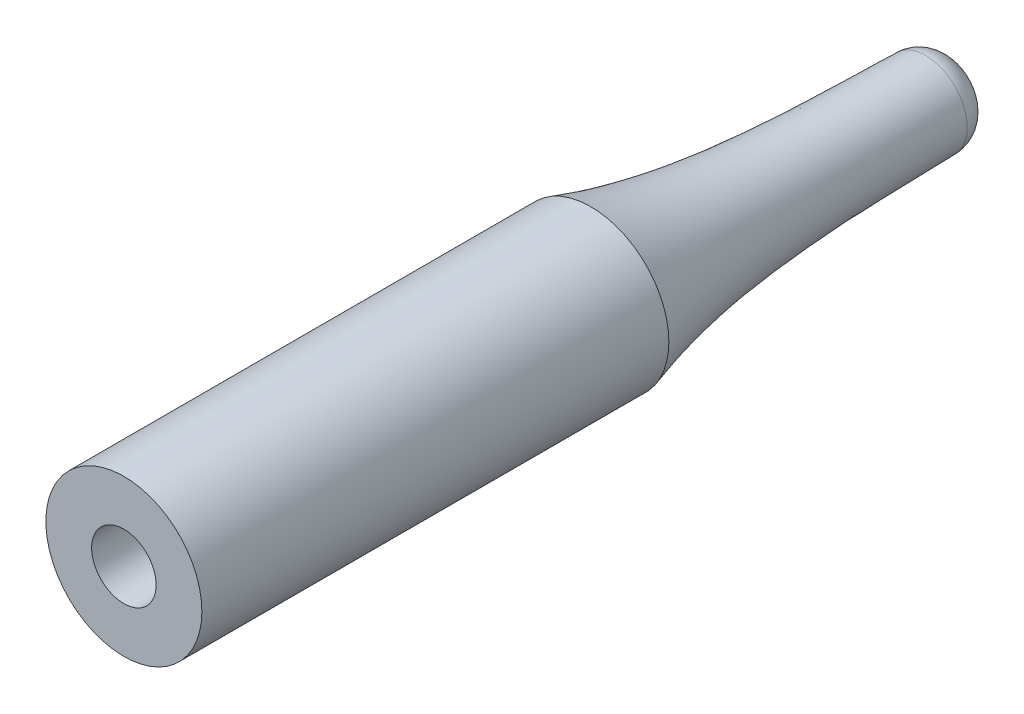
SolidWorks part; units mm, degrees
material "ABS"
ref_plane "Front Plane" through (0, 0, 0) normal (0, 0, 1) x (1, 0, 0)
ref_plane "Top Plane" through (0, 0, 0) normal (0, 1, 0) x (1, 0, 0)
ref_plane "Right Plane" through (0, 0, 0) normal (1, 0, 0) x (0, 0, -1)
sketch "Sketch1" plane through (0, 0, 0) normal (0, 1, 0) x (1, 0, 0)
  line L0 (2.971, 21.3699) -> (0, 21.3699)
  line L1 (0, 21.3699) -> (0, -31.8579)
  line L2 (2.3495, -38.9699) -> (2.3495, -31.8579)
  line L3 (2.3495, -31.8579) -> (0, -31.8579)
  line L5 (0, 21.3699) -> (0, -4.9699) construction
  line L6 (5.68, -4.9699) -> (5.68, -38.9699)
  line L7 (2.3495, -38.9699) -> (5.68, -38.9699)
  spline S0 degree 3 poles (2.971, 21.3699) (3.2225, 12.6396) (2.9713, 3.4911) (5.68, -4.9699) knots 0 0 0 0 1 1 1 1
  dimension "D1" = 5.68
  dimension "D2" = 34
  dimension "D3" = 7.112
  dimension "D4" = 26.3398
revolve "Revolve1" add sketch "Sketch1" angle 360 about L5
fillet "Fillet1" radius 2 1 edges at (2.971, 0, -21.3699)
